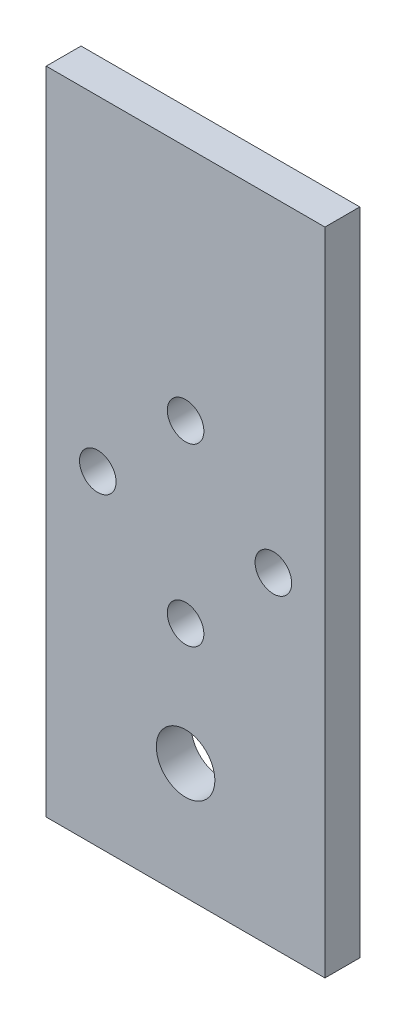
SolidWorks part; units mm, degrees
ref_plane "Front Plane" through (0, 0, 0) normal (0, 0, 1) x (1, 0, 0)
ref_plane "Top Plane" through (0, 0, 0) normal (0, 1, 0) x (1, 0, 0)
ref_plane "Right Plane" through (0, 0, 0) normal (1, 0, 0) x (0, 0, -1)
sketch "Sketch1" plane through (0, 0, 0) normal (0, 0, 1) x (1, 0, 0)
  line L0 (7.05, 44.45) -> (31.05, 44.45) construction
  line L1 (0, 0) -> (38.1, 0)
  line L2 (0, 0) -> (0, 88.9)
  line L3 (0, 88.9) -> (38.1, 88.9)
  line L4 (38.1, 0) -> (38.1, 88.9)
  line L5 (19.05, 56.45) -> (19.05, 32.45) construction
  circle A0 centre (19.05, 56.45) radius 2.5
  circle A1 centre (31.05, 44.45) radius 2.5
  circle A2 centre (19.05, 32.45) radius 2.5
  circle A3 centre (7.05, 44.45) radius 2.5
  circle A4 centre (19.05, 15.875) radius 4
  point P13 (38.1, 44.45)
  point P14 (19.05, 88.9)
  point P17 (19.05, 0)
  dimension "D3" = 5
  dimension "D8" = 8
  dimension "D1" = 38.1
  dimension "D2" = 88.9
  dimension "D4" = 12
  dimension "D5" = 12
  dimension "D6" = 12
  dimension "D7" = 12
  dimension "D9" = 28.575
extrude "Boss-Extrude1" add sketch "Sketch1" along normal blind 4.7625
